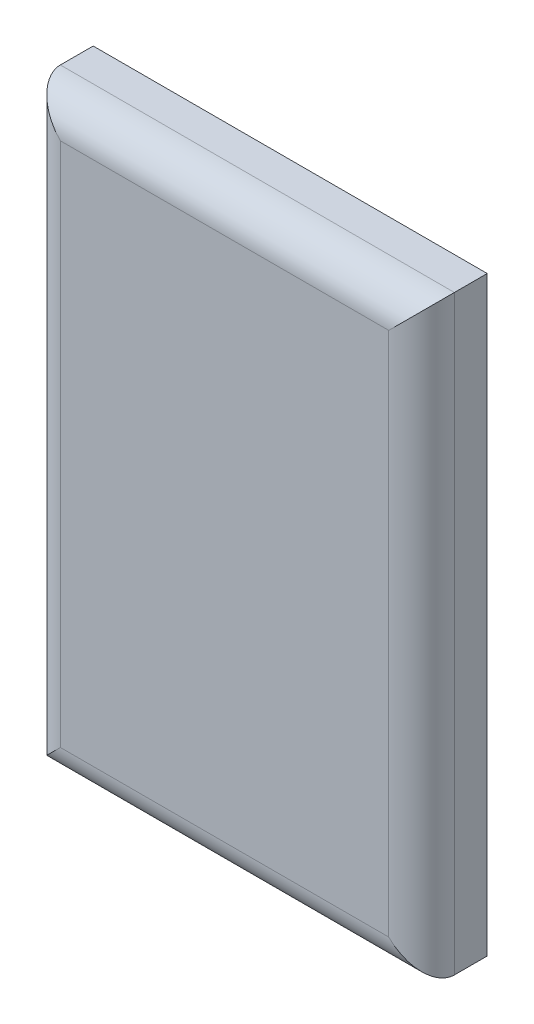
SolidWorks part; units mm, degrees
ref_plane "Front Plane" through (0, 0, 0) normal (0, 0, 1) x (1, 0, 0)
ref_plane "Top Plane" through (0, 0, 0) normal (0, 1, 0) x (1, 0, 0)
ref_plane "Right Plane" through (0, 0, 0) normal (1, 0, 0) x (0, 0, -1)
sketch "Sketch1" plane through (0, 0, 0) normal (0, 0, 1) x (1, 0, 0)
  line L1 (-76.2, -114.3) -> (76.2, -114.3)
  line L2 (-76.2, -114.3) -> (-76.2, 114.3)
  line L3 (-76.2, 114.3) -> (76.2, 114.3)
  line L4 (76.2, -114.3) -> (76.2, 114.3)
  line L5 (-76.2, -114.3) -> (76.2, 114.3) construction
  line L6 (-76.2, 114.3) -> (76.2, -114.3) construction
  point P0 (0, 0)
  dimension "D1" = 228.6
  dimension "D2" = 152.4
extrude "Boss-Extrude1" add sketch "Sketch1" along normal blind 25.4
fillet "Fillet1" radius 12.7 4 edges at (0, -114.3, 25.4) (-76.2, 0, 25.4) (0, 114.3, 25.4) (76.2, 0, 25.4)
